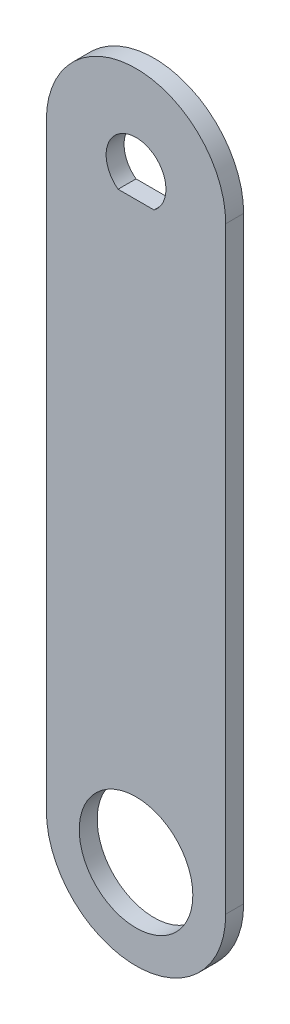
SolidWorks part; units mm, degrees
ref_plane "前视基准面" through (0, 0, 0) normal (0, 0, 1) x (1, 0, 0)
ref_plane "上视基准面" through (0, 0, 0) normal (0, 1, 0) x (1, 0, 0)
ref_plane "右视基准面" through (0, 0, 0) normal (1, 0, 0) x (0, 0, -1)
sketch "草图1" plane through (0, 0, 0) normal (0, 0, 1) x (1, 0, 0)
  line L0 (-15, 0) -> (-15, -100)
  line L1 (15, 0) -> (15, -100)
  line L3 (0, -55) -> (0, 55) construction
  line L4 (0, -4) -> (3, -4)
  line L5 (0, -4) -> (-3, -4)
  arc A0 (15, 0) -> (-15, 0) centre (0, 0) ccw
  arc A1 (-15, -100) -> (15, -100) centre (0, -100) ccw
  circle A2 centre (0, -100) radius 9.5
  arc A3 (3, -4) -> (-3, -4) centre (0, 0) ccw
extrude "凸台-拉伸1" add sketch "草图1" along normal blind 3
